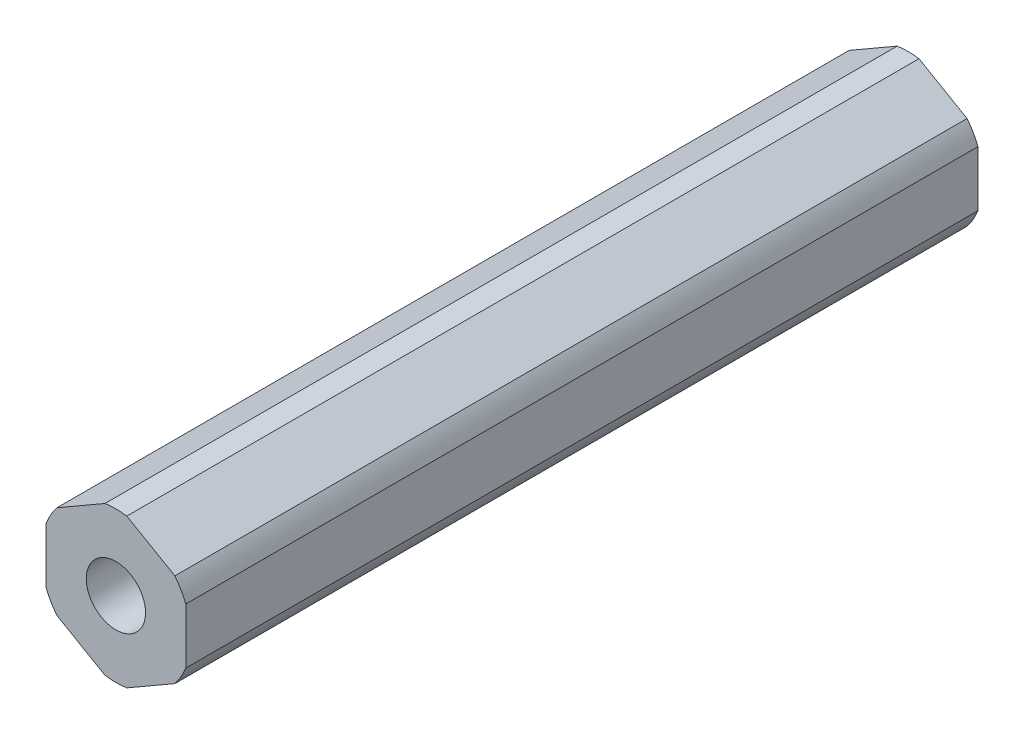
SolidWorks part; units mm, degrees
material "7075-T6 (SN)"
ref_plane "Front Plane" through (0, 0, 0) normal (0, 0, 1) x (1, 0, 0)
ref_plane "Top Plane" through (0, 0, 0) normal (0, 1, 0) x (1, 0, 0)
ref_plane "Right Plane" through (0, 0, 0) normal (1, 0, 0) x (0, 0, -1)
sketch "Sketch1" plane through (0, 0, 0) normal (0, 0, 1) x (1, 0, 0)
  line L1 (4.7625, 2.7496) -> (0, 5.4993)
  line L2 (0, 5.4993) -> (-4.7625, 2.7496)
  line L3 (-4.7625, 2.7496) -> (-4.7625, -2.7496)
  line L4 (-4.7625, -2.7496) -> (0, -5.4993)
  line L5 (0, -5.4993) -> (4.7625, -2.7496)
  line L6 (4.7625, -2.7496) -> (4.7625, 2.7496)
  circle A0 centre (0, 0) radius 4.7625 construction
  circle A1 centre (0, 0) radius 5.1245
  dimension "D1" = 10.2489
  dimension "D2" = 9.525
extrude "Boss-Extrude1" add sketch "Sketch1" along normal mid plane 53.975 contours L6 A1 L1 L2 L3 L4 L5
sketch "Sketch2" plane through (0, 0, -26.9875) normal (0, 0, -1) x (-1, 0, 0)
  circle A0 centre (0, 0) radius 2.0193
  dimension "D1" = 4.0386
extrude "Cut-Extrude1" cut sketch "Sketch2" against normal blind 19.05
mirror "Mirror1" about plane through (0, 0, 0) normal (0, 0, 1) of "Cut-Extrude1"
